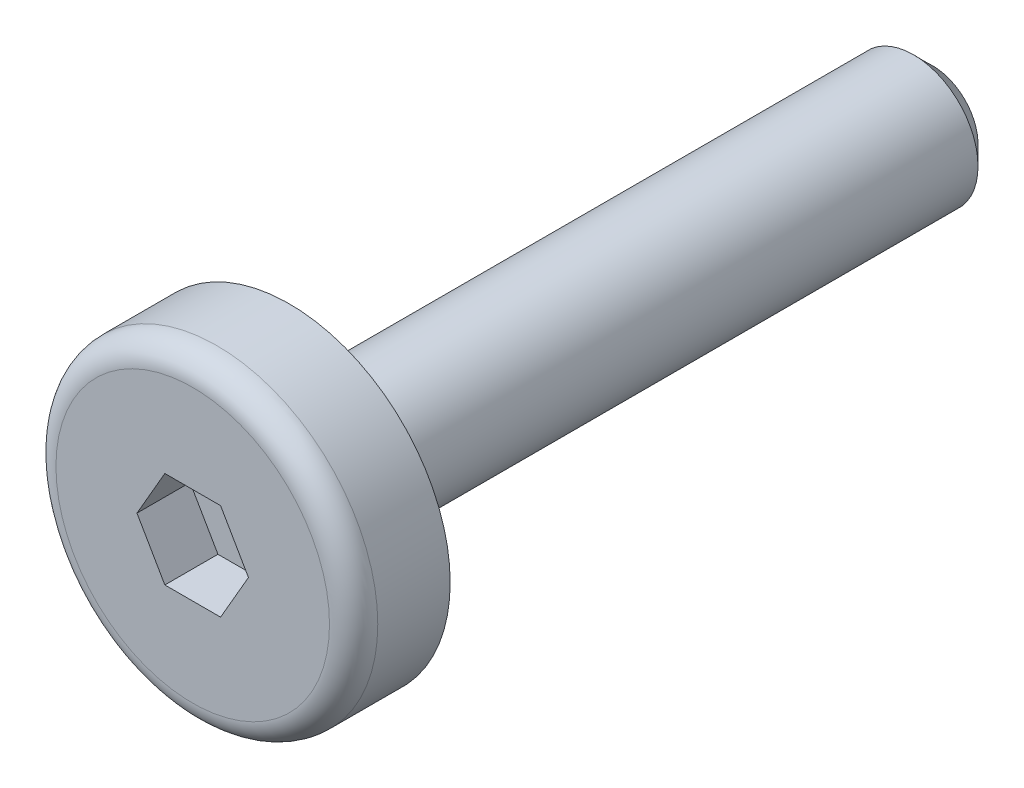
SolidWorks part; units mm, degrees
ref_plane "Front Plane" through (0, 0, 0) normal (0, 0, 1) x (1, 0, 0)
ref_plane "Top Plane" through (0, 0, 0) normal (0, 1, 0) x (1, 0, 0)
ref_plane "Right Plane" through (0, 0, 0) normal (1, 0, 0) x (0, 0, -1)
sketch "Screw Section" plane through (0, 0, 0) normal (0, 1, 0) x (1, 0, 0)
  line L0 (0, 10) -> (1, 10)
  line L1 (1, 10) -> (1, 0)
  line L2 (1, 0) -> (2.5, 0)
  line L3 (2.5, 0) -> (2.5, -1.5)
  line L4 (2.5, -1.5) -> (0, -1.5)
  line L5 (0, -1.5) -> (0, 10)
  line L6 (0, -10.123) -> (0, 10.123) construction
  dimension "D1" = 1
  dimension "D2" = 2.5
  dimension "D3" = 10
  dimension "D4" = 1.5
  dimension "D5" = 10.123
  dimension "D6" = 10.123
revolve "Screw Blank Revolve" add sketch "Screw Section" angle 360 about L6
chamfer "Shank Tip Chamfer" distance 0.3 1 edges at (1, 0, -10)
fillet "Pan Head Round" radius 0.375 1 edges at (2.5, 0, 1.5)
ref_plane "Head Crown Plane" through (0, 0, 1.5) normal (0, 0, 1) x (1, 0, 0)
sketch "Hex Drive Sketch" plane through (0, 0, 1.5) normal (0, 0, 1) x (1, 0, 0)
  line L1 (0.866, 0) -> (0.433, 0.75)
  line L2 (0.433, 0.75) -> (-0.433, 0.75)
  line L3 (-0.433, 0.75) -> (-0.866, 0)
  line L4 (-0.866, 0) -> (-0.433, -0.75)
  line L5 (-0.433, -0.75) -> (0.433, -0.75)
  line L6 (0.433, -0.75) -> (0.866, 0)
  circle A0 centre (0, 0) radius 0.75 construction
  dimension "D1" = 1.5
extrude "Hex Drive Cut" cut sketch "Hex Drive Sketch" against normal blind 0.825
equation "\"nominal_length\"= 10.0mm 'Screw length: under pan head or including flat head"
equation "\"model_shank_radius\"= 1mm 'Clearance envelope minor shank radius; thread is not modeled"
equation "\"head_diameter\"= 5mm 'Head outside diameter"
equation "\"head_height\"= 1.5mm 'Head axial height"
equation "\"drive_across_flats\"= 1.5mm 'Hex drive across flats"
equation "\"tip_chamfer\"= 0.3mm 'Shank tip chamfer"
equation "\"head_round\"= 0.375mm 'Pan head crown edge radius"
equation "\"drive_depth\"= 0.8250000000000001mm 'Hex socket depth"
equation "\"axis_reference_halfspan\"= 10.123mm 'Half display length of the construction axis; avoids sharing a profile endpoint"
equation "\"full_turn\"= 360deg 'Full circular extent for revolves and patterns"
equation "\"D1@Screw Section\"= \"model_shank_radius\""
equation "\"D2@Screw Section\"= \"head_diameter\" / 2"
equation "\"D3@Screw Section\"= \"nominal_length\""
equation "\"D4@Screw Section\"= \"head_height\""
equation "\"D5@Screw Section\"= \"axis_reference_halfspan\""
equation "\"D6@Screw Section\"= \"axis_reference_halfspan\""
equation "\"D1@Screw Blank Revolve\"= \"full_turn\""
equation "\"D1@Shank Tip Chamfer\"= \"tip_chamfer\""
equation "\"D1@Pan Head Round\"= \"head_round\""
equation "\"D1@Head Crown Plane\"= \"head_height\""
equation "\"D1@Hex Drive Sketch\"= \"drive_across_flats\""
equation "\"D1@Hex Drive Cut\"= \"drive_depth\""
